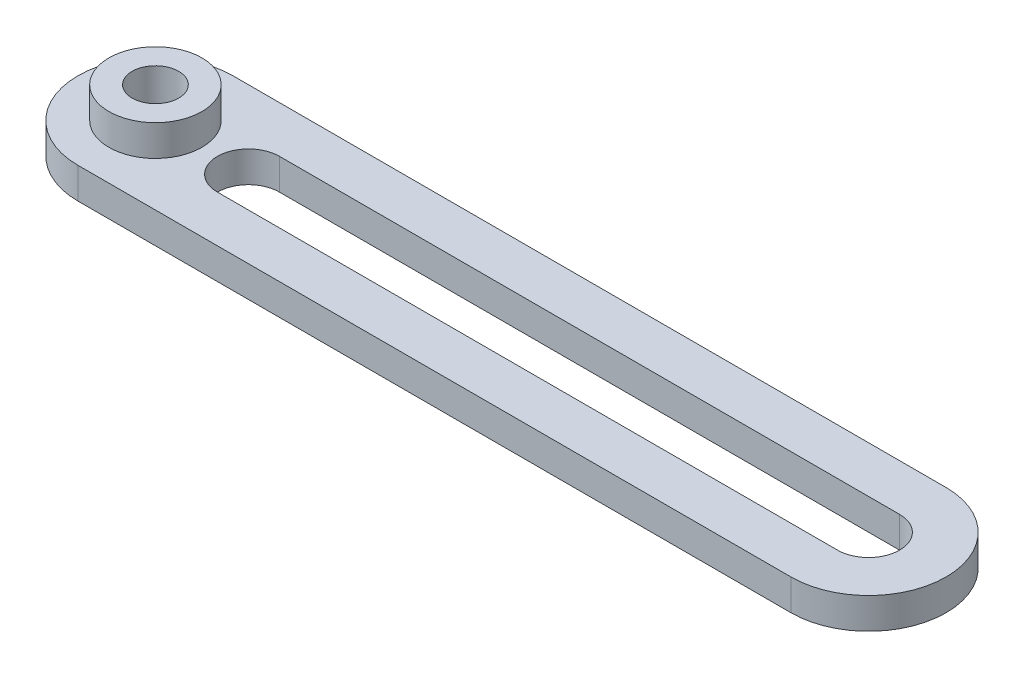
SolidWorks part; units mm, degrees
ref_plane "Front Plane" through (0, 0, 0) normal (0, 0, 1) x (1, 0, 0)
ref_plane "Top Plane" through (0, 0, 0) normal (0, 1, 0) x (1, 0, 0)
ref_plane "Right Plane" through (0, 0, 0) normal (1, 0, 0) x (0, 0, -1)
sketch "Sketch2" plane through (0, 0, 0) normal (0, 1, 0) x (1, 0, 0)
  line L0 (-190, 0) -> (0, 0) construction
  line L5 (-190, 10) -> (0, 10)
  line L6 (-190, -10) -> (0, -10)
  line L7 (-230, 0) -> (135, 0) construction
  line L8 (-230, 25) -> (0, 25)
  line L9 (-230, -25) -> (0, -25)
  line L10 (-200, 10) -> (-190, 10)
  line L11 (-200, -10) -> (-190, -10)
  arc A5 (0, -10) -> (0, 10) centre (0, 0) ccw
  arc A6 (-230, 25) -> (-230, -25) centre (-230, 0) ccw
  circle A9 centre (-230, 0) radius 7.5
  arc A10 (0, 25) -> (0, -25) centre (0, 0) cw
  arc A11 (-200, 10) -> (-200, -10) centre (-200, 0) ccw
  point P2 (0, 0)
  point P8 (0, 0)
  point P10 (0, 0)
  point P11 (0, 29.878)
  point P13 (-104.7152, -12.2996)
  point P15 (0, 0)
  point P21 (0, 0)
  dimension "D3" = 50
  dimension "D5" = 15
  dimension "D6" = 10
  dimension "D2" = 230
  dimension "D1" = 20
  dimension "D4" = 190
extrude "Boss-Extrude1" add sketch "Sketch2" along normal blind 10
sketch "Sketch3" plane through (0, 0, 0) normal (0, -1, 0) x (1, 0, 0)
  circle A0 centre (-230, 0) radius 15
  circle A1 centre (-230, 0) radius 7.5 construction
  circle A2 centre (-230, 0) radius 7.5
  dimension "D1" = 30
extrude "Boss-Extrude2" add sketch "Sketch3" against normal blind 20
